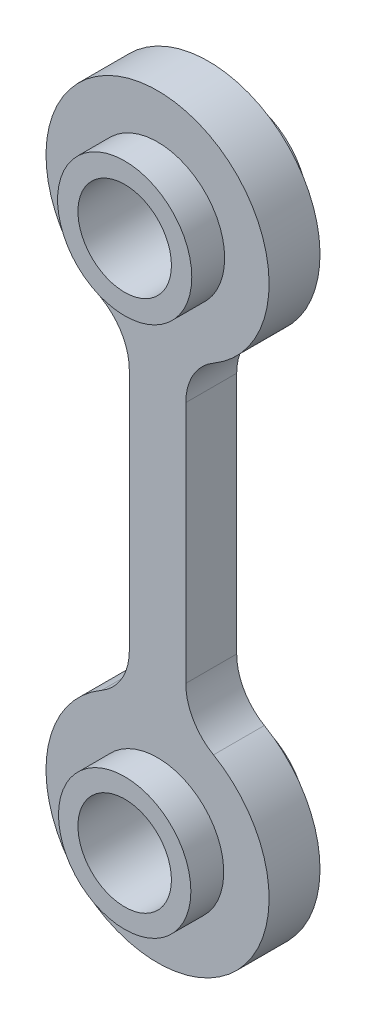
SolidWorks part; units mm, degrees
material "1060-H18"
ref_plane "Front Plane" through (0, 0, 0) normal (0, 0, 1) x (1, 0, 0)
ref_plane "Top Plane" through (0, 0, 0) normal (0, 1, 0) x (1, 0, 0)
ref_plane "Right Plane" through (0, 0, 0) normal (1, 0, 0) x (0, 0, -1)
sketch "Sketch1" plane through (0, 0, 0) normal (0, 0, 1) x (1, 0, 0)
  circle A0 centre (0, 0) radius 5.05
  circle A1 centre (0, 0) radius 7.15
  dimension "D1" = 10.1
  dimension "D2" = 14.3
extrude "Boss-Extrude1" add sketch "Sketch1" along normal blind 12.6
ref_plane "Plane1" through (0, 0, 6.3) normal (0, 0, -1) x (-1, 0, 0)
sketch "Sketch2" plane through (0, 0, 6.3) normal (0, 0, -1) x (-1, 0, 0)
  line L0 (0, 0) -> (0, 57.5) construction
  line L1 (3.05, 15.6173) -> (3.05, 41.8827)
  line L2 (-3.05, 15.6173) -> (-3.05, 41.8827)
  line L3 (-3.05, 0) -> (-3.05, 57.5) construction
  line L4 (3.05, 0) -> (3.05, 57.5) construction
  arc A0 (-6.0417, 10.426) -> (6.0417, 10.426) centre (0, 0) ccw
  circle A1 centre (0, 57.5) radius 7.2
  arc A2 (6.0417, 47.074) -> (-6.0417, 47.074) centre (0, 57.5) ccw
  arc A3 (3.05, 41.8827) -> (6.0417, 47.074) centre (9.05, 41.8827) cw
  arc A4 (-3.05, 41.8827) -> (-6.0417, 47.074) centre (-9.05, 41.8827) ccw
  arc A5 (3.05, 15.6173) -> (6.0417, 10.426) centre (9.05, 15.6173) ccw
  arc A6 (-3.05, 15.6173) -> (-6.0417, 10.426) centre (-9.05, 15.6173) cw
  circle A7 centre (0, 0) radius 7.15
  dimension "D1" = 24.1
  dimension "D2" = 14.4
  dimension "D3" = 24.1
  dimension "D6" = 6
  dimension "D4" = 3.05
  dimension "D5" = 3.05
extrude "Boss-Extrude2" add sketch "Sketch2" along normal blind 2.75 and the other way blind 2.75
sketch "Sketch3" plane through (0, 0, 3.55) normal (0, 0, -1) x (-1, 0, 0)
  circle A0 centre (0, 57.5) radius 7.2482
  circle A1 centre (0, 57.5) radius 5.05
  dimension "D1" = 10.1
extrude "Boss-Extrude3" add sketch "Sketch3" along normal up to surface and the other way up to surface up to face at (7.15, 0, 0) other way up to face at (7.15, 0, 12.6)
